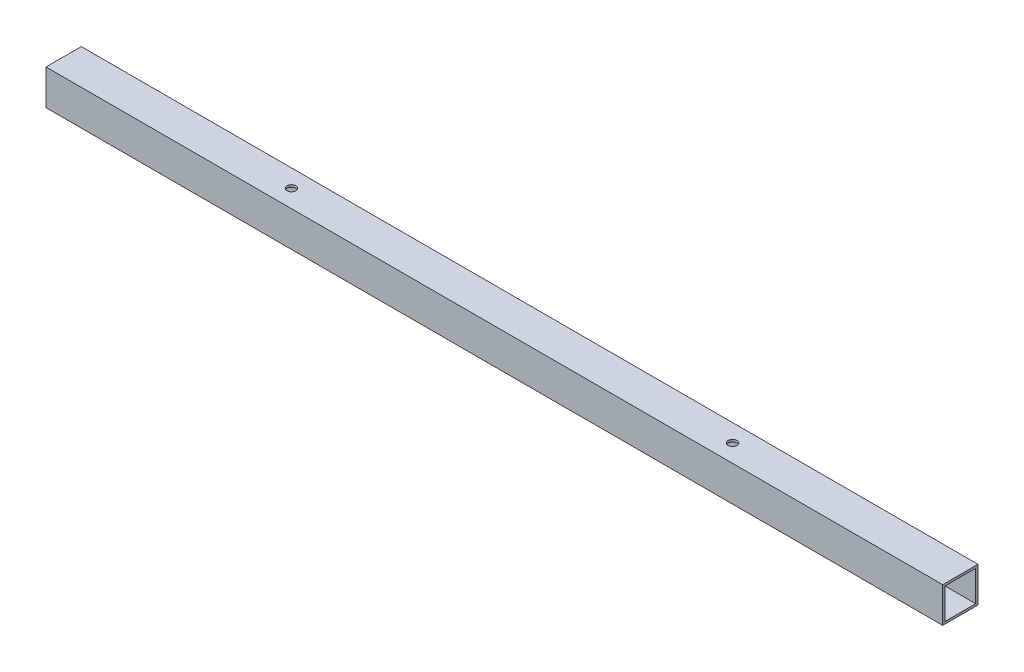
SolidWorks part; units mm, degrees
ref_plane "Front Plane" through (0, 0, 0) normal (0, 0, 1) x (1, 0, 0)
ref_plane "Top Plane" through (0, 0, 0) normal (0, 1, 0) x (1, 0, 0)
ref_plane "Right Plane" through (0, 0, 0) normal (1, 0, 0) x (0, 0, -1)
sketch "Sketch1" plane through (0, 0, 0) normal (0, 1, 0) x (1, 0, 0)
  line L0 (0, 0) -> (645.4, 0)
  dimension "D1" = 645.4
other "Al tube square AL TUBE 1 SQR X 0.065 WALL(1)"
ref_plane "Plane2" through (0, 0, 0) normal (1, 0, 0) x (0, 0, -1)
sketch "Sketch16" plane through (0, 0, 0) normal (1, 0, 0) x (0, 0, -1)
  line L0 (-11.049, -11.049) -> (-11.049, 11.049)
  line L1 (11.049, 11.049) -> (-11.049, 11.049)
  line L2 (11.049, 11.049) -> (11.049, -11.049)
  line L3 (-11.049, -11.049) -> (11.049, -11.049)
  line L4 (-12.7, -12.7) -> (12.7, -12.7)
  line L5 (-12.7, -12.7) -> (-12.7, 12.7)
  line L6 (12.7, 12.7) -> (-12.7, 12.7)
  line L7 (12.7, 12.7) -> (12.7, -12.7)
  line L8 (0, -11.049) -> (0, -12.7) construction
  line L9 (0, -11.049) -> (0, 11.049) construction
  line L10 (0, 11.049) -> (0, 12.7) construction
  line L11 (12.7, 0) -> (11.049, 0) construction
  line L12 (11.049, 0) -> (-11.049, 0) construction
  line L13 (-11.049, 0) -> (-12.7, 0) construction
  point P14 (0, 0)
  point P17 (0, 0)
  dimension "Thickness" = 1.651
  dimension "V_leg" = 25.4
  dimension "H_leg" = 25.4
sketch "Sketch17" plane through (0, 12.7, 0) normal (0, 1, 0) x (1, 0, 0)
  line L0 (322.7, 12.7) -> (322.7, -12.7) construction
  line L1 (645.4, 12.7) -> (0, 12.7) construction
  line L2 (645.4, -12.7) -> (0, -12.7) construction
  line L3 (0, 0) -> (645.4, 0) construction
  line L4 (645.4, 12.7) -> (645.4, -12.7) construction
  point P6 (163.95, 0)
  point P12 (0, 0)
  point P13 (481.45, 0)
  dimension "D1" = 158.75
hole_wizard "1/4 (0.25) Diameter Hole1" positions "Sketch17" profile "Sketch18" hole size "1/4" standard "ANSI Inch" end condition through all
sketch "Sketch18" plane through (481.45, 12.7, 0) normal (1, 0, 0) x (0, 0, 1)
  line L0 (0, 0) -> (0, 25.4)
  line L1 (0, 25.4) -> (3.175, 25.4)
  line L2 (3.175, 25.4) -> (3.175, 0)
  line L5 (3.175, 0) -> (0, 0)
  line L11 (0, -6.35) -> (0, 107.95) construction
  dimension "Thru Hole Dia." = 6.35
  dimension "Thru Hole Depth" = 25.4
equation "\"D1@Sketch17\"=(17.5in/2)-2.5in"
